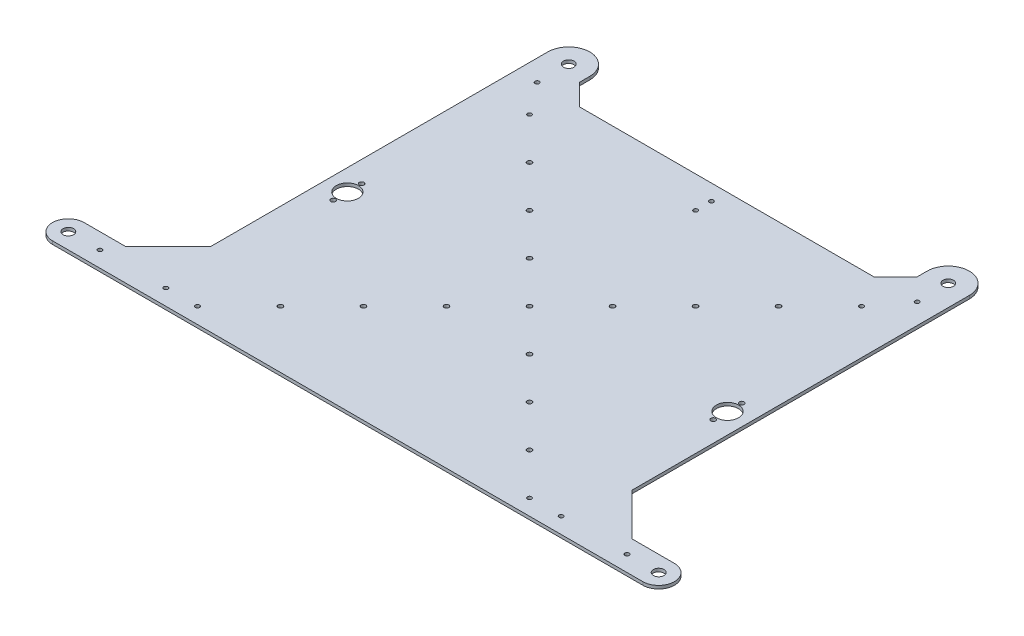
SolidWorks part; units mm, degrees
ref_plane "Front Plane" through (0, 0, 0) normal (0, 0, 1) x (1, 0, 0)
ref_plane "Top Plane" through (0, 0, 0) normal (0, 1, 0) x (1, 0, 0)
ref_plane "Right Plane" through (0, 0, 0) normal (1, 0, 0) x (0, 0, -1)
sketch "Sketch1" plane through (0, 0, 0) normal (0, 1, 0) x (1, 0, 0)
  line L0 (0, 0) -> (0, -157.5) construction
  line L1 (0, -157.5) -> (-280, -157.5) construction
  line L2 (0, -157.5) -> (280, -157.5) construction
  line L3 (-200.2852, -142.5) -> (199.7148, -142.5) construction
  line L4 (-200.2852, -142.5) -> (-280, -142.5)
  line L5 (-157.5, 157.5) -> (157.5, -157.5) construction
  line L6 (-157.5, -157.5) -> (157.5, 157.5) construction
  line L7 (-200.2852, -142.5) -> (-200.2852, 187.5)
  line L8 (-160.2852, 187.5) -> (199.7148, 187.5)
  line L9 (199.7148, 187.5) -> (199.7148, -142.5)
  line L10 (-280, -172.5) -> (280, -172.5)
  line L11 (-180.2852, 172.5) -> (-180.2852, -157.5) construction
  line L12 (280, -142.5) -> (199.7148, -142.5)
  line L13 (-200.2852, 187.5) -> (-200.2852, 217.5)
  line L15 (-160.2852, 217.5) -> (-160.2852, 187.5)
  circle A0 centre (-157.5, 157.5) radius 2
  circle A1 centre (157.5, 157.5) radius 2
  circle A2 centre (157.5, -157.5) radius 2
  circle A3 centre (-157.5, -157.5) radius 2
  circle A4 centre (-280, -157.5) radius 5
  circle A5 centre (280, -157.5) radius 5
  arc A6 (-280, -142.5) -> (-280, -172.5) centre (-280, -157.5) ccw
  arc A7 (280, -172.5) -> (280, -142.5) centre (280, -157.5) ccw
  circle A8 centre (-250, -157.5) radius 2
  circle A9 centre (250, -157.5) radius 2
  circle A15 centre (-180.2852, 7.5) radius 10.5
  circle A16 centre (-180.2852, 21) radius 2.25
  circle A17 centre (-180.2852, -6) radius 2.25
  circle A18 centre (180.2852, -6) radius 2.25
  circle A19 centre (180.2852, 21) radius 2.25
  circle A20 centre (180.2852, 7.5) radius 10.5
  circle A21 centre (-180.2852, 217.5) radius 5
  arc A22 (-200.2852, 217.5) -> (-160.2852, 217.5) centre (-180.2852, 217.5) cw
  point P0 (0, 0)
  dimension "D3" = 445.4773
  dimension "D2" = 4
  dimension "D6" = 10
  dimension "D8" = 30
  dimension "D18" = 21
  dimension "D21" = 4.5
  dimension "D1" = 315
  dimension "D4" = 445.4773
  dimension "D9" = 30
  dimension "D10" = 400
  dimension "D11" = 20
  dimension "D12" = 15
  dimension "D17" = 330
  dimension "D19" = 27
  dimension "D20" = 13.5
  dimension "D23" = 280
extrude "Boss-Extrude1" add sketch "Sketch1" along normal blind 3
sketch "Sketch2" plane through (0, 3, 0) normal (0, 1, 0) x (1, 0, 0)
  line L0 (199.7148, 187.5) -> (199.7148, 217.5)
  line L1 (159.7148, 217.5) -> (159.7148, 187.5)
  line L2 (199.7148, 187.5) -> (-160.2852, 187.5) construction
  line L3 (199.7148, 187.5) -> (159.7148, 187.5)
  arc A0 (199.7148, 217.5) -> (159.7148, 217.5) centre (179.7148, 217.5) ccw
  circle A1 centre (179.7148, 217.5) radius 5
  circle A2 centre (179.7148, 172.5) radius 5 construction
  dimension "D1" = 20
  dimension "D2" = 0
extrude "Boss-Extrude2" add sketch "Sketch2" against normal up to surface (3 mm away) up to face at (-32.1711, 0, 8.5)
chamfer "Chamfer2" distance 20 angle 45 2 edges at (-160.2852, 1.5, -187.5) (159.7148, 1.5, -187.5)
chamfer "Chamfer3" distance 40 angle 45 2 edges at (199.7148, 1.5, 142.5) (-200.2852, 1.5, 142.5)
sketch "Sketch3" plane through (0, 3, 0) normal (0, 1, 0) x (1, 0, 0)
  line L0 (-180.2852, 217.5) -> (-180.2852, 187.5) construction
  circle A0 centre (-180.2852, 187.5) radius 2
  circle A1 centre (-250, -157.5) radius 2 construction
  dimension "D1" = 30
extrude "Cut-Extrude1" cut sketch "Sketch3" against normal blind 10
mirror "Mirror1" about plane through (0, 0, 0) normal (1, 0, 0) of "Cut-Extrude1"
sketch "Sketch5" plane through (0, 3, 0) normal (0, 1, 0) x (1, 0, 0)
  line L1 (0, 0) -> (39.375, -39.375) construction
  line L2 (39.375, -39.375) -> (78.75, -78.75) construction
  line L3 (78.75, -78.75) -> (118.125, -118.125) construction
  line L4 (118.125, -118.125) -> (157.5, -157.5) construction
  circle A0 centre (118.125, -118.125) radius 2.25
  circle A1 centre (78.75, -78.75) radius 2.25
  circle A2 centre (39.375, -39.375) radius 2.25
  circle A3 centre (-39.375, -39.375) radius 2.25
  circle A4 centre (-78.75, -78.75) radius 2.25
  circle A5 centre (-118.125, -118.125) radius 2.25
  circle A6 centre (-39.375, 39.375) radius 2.25
  circle A7 centre (-78.75, 78.75) radius 2.25
  circle A8 centre (-118.125, 118.125) radius 2.25
  circle A9 centre (39.375, 39.375) radius 2.25
  circle A10 centre (78.75, 78.75) radius 2.25
  circle A11 centre (118.125, 118.125) radius 2.25
  circle A12 centre (0, 0) radius 2.25
  point P32 (0, 0)
  dimension "D1" = 4.5
  dimension "D2" = 4
extrude "Cut-Extrude2" cut sketch "Sketch5" against normal blind 10
sketch "Sketch6" plane through (0, 3, 0) normal (0, 1, 0) x (1, 0, 0)
  line L0 (-157.5, 157.5) -> (157.5, 157.5) construction
  line L1 (-157.5, -157.5) -> (-187.5, -157.5) construction
  line L2 (0, -172.5) -> (0, -106.4898) construction
  line L3 (-280, -172.5) -> (280, -172.5) construction
  circle A0 centre (0, 157.5) radius 2
  circle A1 centre (157.5, 157.5) radius 2 construction
  circle A2 centre (-187.5, -157.5) radius 2
  circle A3 centre (-157.5, -157.5) radius 2 construction
  circle A4 centre (187.5, -157.5) radius 2
  dimension "D1" = 30
extrude "Cut-Extrude3" cut sketch "Sketch6" against normal blind 171
sketch "Sketch7" plane through (0, 3, 0) normal (0, 1, 0) x (1, 0, 0)
  circle A0 centre (0, 172.5) radius 2
  circle A1 centre (0, 157.5) radius 2 construction
extrude "Cut-Extrude4" cut sketch "Sketch7" against normal blind 22
